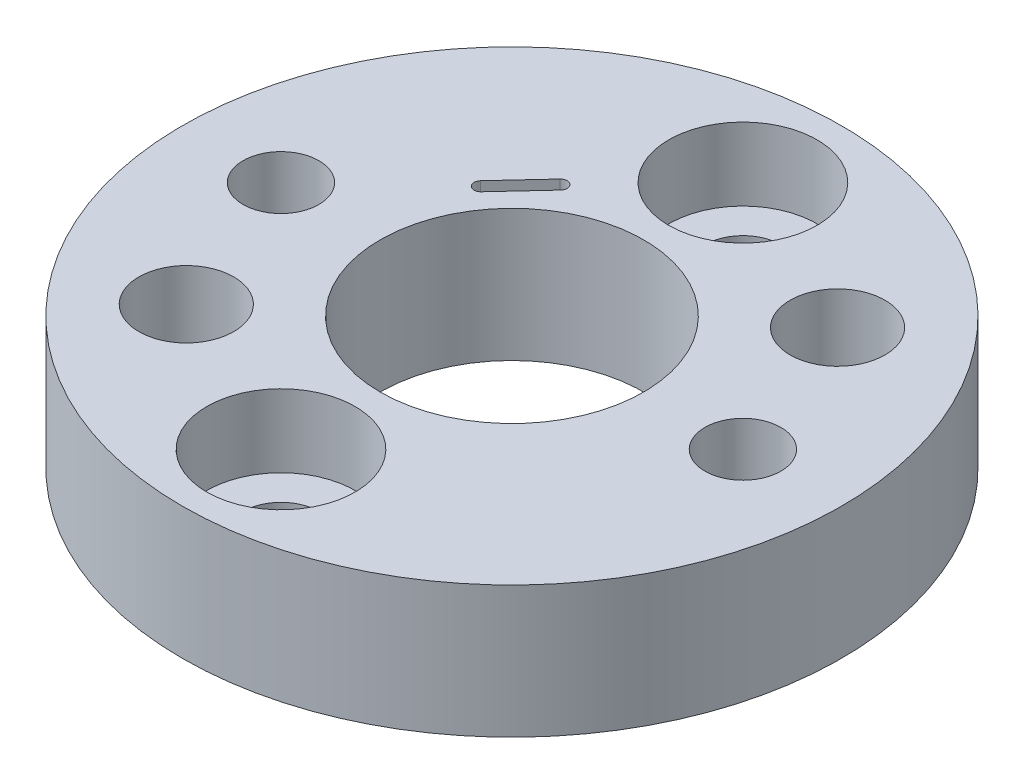
SolidWorks part; units mm, degrees
ref_plane "Front Plane" through (0, 0, 0) normal (0, 0, 1) x (1, 0, 0)
ref_plane "Top Plane" through (0, 0, 0) normal (0, 1, 0) x (1, 0, 0)
ref_plane "Right Plane" through (0, 0, 0) normal (1, 0, 0) x (0, 0, -1)
sketch "Sketch1" plane through (0, 0, 0) normal (0, 1, 0) x (1, 0, 0)
  circle A0 centre (0, 0) radius 15.875
  dimension "D1" = 31.75
extrude "Boss-Extrude1" add sketch "Sketch1" along normal blind 6.35
sketch "Sketch2" plane through (0, 6.35, 0) normal (0, 1, 0) x (1, 0, 0)
  circle A0 centre (0, 0) radius 6.35
  dimension "D1" = 12.7
extrude "Cut-Extrude1" cut sketch "Sketch2" against normal through all
sketch "Sketch5" plane through (0, 6.35, 0) normal (0, 1, 0) x (1, 0, 0)
  line L0 (0, 0) -> (0, 11.1252)
  line L1 (0, 0) -> (11.1252, 0)
  line L2 (0, 0) -> (0, 11.1252)
  dimension "D1" = 11.1252
  dimension "D2" = 11.1252
sketch "Sketch11" plane through (0, 6.35, 0) normal (0, 1, 0) x (1, 0, 0)
  line L0 (0, 0) -> (8.3289, 7.3564)
  circle A0 centre (8.3289, 7.3564) radius 2.286
  dimension "D2" = 4.572
  dimension "D1" = 11.1125
extrude "Cut-Extrude2" cut sketch "Sketch11" against normal through all contours A0
pattern_circular "CirPattern3" count 2 every 180 about axis through (0, 0, 0) along (0, 1, 0) of "Cut-Extrude2"
sketch "Sketch12" plane through (0, 6.35, 0) normal (0, 1, 0) x (1, 0, 0)
  line L0 (-4.3143, 6.6475) -> (-6.1577, 4.6609)
  line L1 (-4.3143, 6.6475) -> (-5.236, 5.6542)
  line L2 (-6.1577, 4.6609) -> (-4.3143, 6.6475) construction
  line L7 (-6.3976, 4.8835) -> (-4.5542, 6.8701)
  line L8 (-5.9178, 4.4383) -> (-4.0744, 6.4249)
  arc A0 (-6.3976, 4.8835) -> (-5.9178, 4.4383) centre (-6.1577, 4.6609) ccw
  arc A1 (-4.0744, 6.4249) -> (-4.5542, 6.8701) centre (-4.3143, 6.6475) ccw
  point P4 (-5.236, 5.6542)
extrude "Cut-Extrude3" cut sketch "Sketch12" against normal through all contours A0 L8 A1 L7
sketch "Sketch14" plane through (0, 0, 0) normal (0, -1, 0) x (1, 0, 0)
  line L0 (0, 0) -> (11.1252, 0)
hole_wizard "CBORE for #6 Socket Head Cap Screw2" positions "3DSketch3" profile "Sketch16" counterbore size "#6" standard "ANSI Inch" end condition through all
sketch3d "3DSketch3"
  point P0 (11.1252, 0, 0)
sketch "Sketch16" plane through (11.1252, 0, 0) normal (1, 0, 0) x (0, 0, -1)
  line L0 (0, 0) -> (0, 6.35)
  line L1 (0, 6.35) -> (1.8288, 6.35)
  line L3 (1.8288, 6.35) -> (1.8288, 3.5052)
  line L4 (1.8288, 3.5052) -> (3.5725, 3.5052)
  line L5 (3.5725, 3.5052) -> (3.5725, 0)
  line L7 (3.5725, 0) -> (0, 0)
  line L11 (0, -6.35) -> (0, 107.95) construction
  dimension "Thru Hole Dia." = 3.6576
  dimension "Thru Hole Depth" = 6.35
  dimension "C'Bore Dia." = 7.145
  dimension "C'Bore Depth" = 3.5052
hole_wizard "CBORE for #6 Socket Head Cap Screw1" positions "3DSketch4" profile "Sketch17" counterbore size "#6" standard "ANSI Inch" end condition through all
sketch3d "3DSketch4"
  point P0 (0, 6.35, -11.1252)
sketch "Sketch17" plane through (0, 6.35, -11.1252) normal (1, 0, 0) x (0, 0, 1)
  line L0 (0, 0) -> (0, 6.35)
  line L1 (0, 6.35) -> (1.8288, 6.35)
  line L3 (1.8288, 6.35) -> (1.8288, 3.5052)
  line L4 (1.8288, 3.5052) -> (3.5725, 3.5052)
  line L5 (3.5725, 3.5052) -> (3.5725, 0)
  line L7 (3.5725, 0) -> (0, 0)
  line L11 (0, -6.35) -> (0, 107.95) construction
  dimension "Thru Hole Dia." = 3.6576
  dimension "Thru Hole Depth" = 6.35
  dimension "C'Bore Dia." = 7.145
  dimension "C'Bore Depth" = 3.5052
pattern_circular "CirPattern5" count 2 every 180 about axis through (0, 0, 0) along (0, 1, 0) of "CBORE for #6 Socket Head Cap Screw1"
pattern_circular "CirPattern6" count 2 every 180 about axis through (0, 0, 0) along (0, 1, 0) of "CBORE for #6 Socket Head Cap Screw2"
